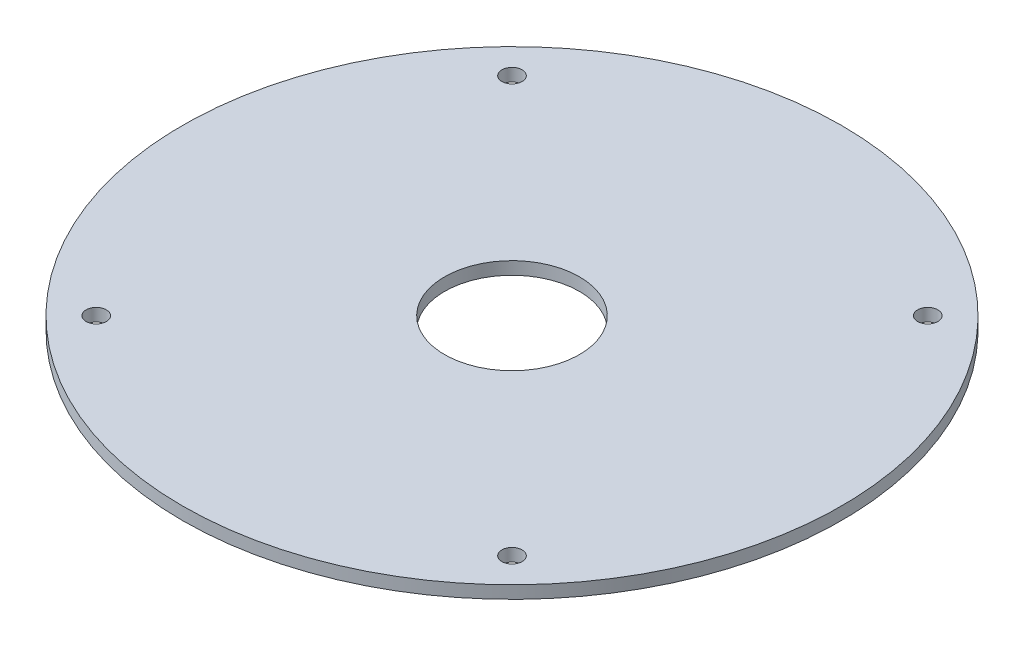
SolidWorks part; units mm, degrees
ref_plane "Front Plane" through (0, 0, 0) normal (0, 0, 1) x (1, 0, 0)
ref_plane "Top Plane" through (0, 0, 0) normal (0, 1, 0) x (1, 0, 0)
ref_plane "Right Plane" through (0, 0, 0) normal (1, 0, 0) x (0, 0, -1)
sketch "Sketch1" plane through (0, 0, 0) normal (0, 1, 0) x (1, 0, 0)
  circle A0 centre (0, 0) radius 65
  dimension "D1" = 130
extrude "Boss-Extrude1" add sketch "Sketch1" along normal blind 2.5
sketch "Sketch2" plane through (0, 0, 0) normal (0, -1, 0) x (1, 0, 0)
  circle A0 centre (0, 0) radius 13.3
  dimension "D1" = 26.6
extrude "Cut-Extrude1" cut sketch "Sketch2" against normal through all
sketch "Sketch3" plane through (0, 0, 0) normal (0, -1, 0) x (1, 0, 0)
  line L1 (41, -41) -> (-41, -41) construction
  line L2 (41, -41) -> (41, 41) construction
  line L3 (41, 41) -> (-41, 41) construction
  line L4 (-41, -41) -> (-41, 41) construction
  line L5 (41, -41) -> (-41, 41) construction
  line L6 (41, 41) -> (-41, -41) construction
  circle A0 centre (-41, 41) radius 2
  circle A1 centre (41, 41) radius 2
  circle A2 centre (41, -41) radius 2
  circle A3 centre (-41, -41) radius 2
  point P0 (0, 0)
  dimension "D3" = 4
  dimension "D4" = 4
  dimension "D5" = 4
  dimension "D6" = 4
  dimension "D1" = 82
  dimension "D2" = 82
extrude "Cut-Extrude2" cut sketch "Sketch3" against normal through all
